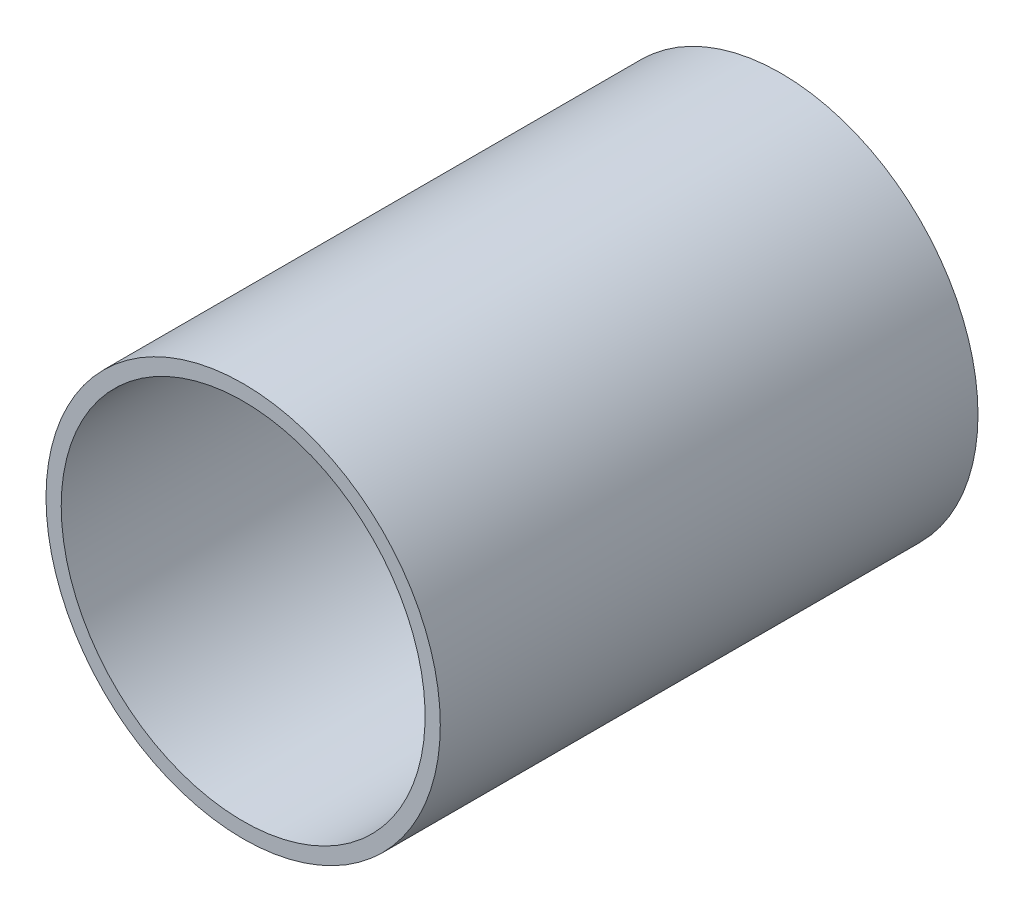
SolidWorks part; units mm, degrees
ref_plane "Front" through (0, 0, 0) normal (0, 0, 1) x (1, 0, 0)
ref_plane "Top" through (0, 0, 0) normal (0, 1, 0) x (1, 0, 0)
ref_plane "Right" through (0, 0, 0) normal (1, 0, 0) x (0, 0, -1)
sketch "Sketch1" plane through (0, 0, 0) normal (0, 0, 1) x (1, 0, 0)
  circle A0 centre (0, 0) radius 33
  dimension "D1" = 66
extrude "Boss-Extrude2" add sketch "Sketch1" along normal blind 90
sketch "Sketch2" plane through (0, 0, 0) normal (0, 0, -1) x (-1, 0, 0)
  circle A1 centre (0, 0) radius 30.4546
  dimension "D1" = 60.9092
extrude "Cut-Extrude1" cut sketch "Sketch2" against normal blind 90
